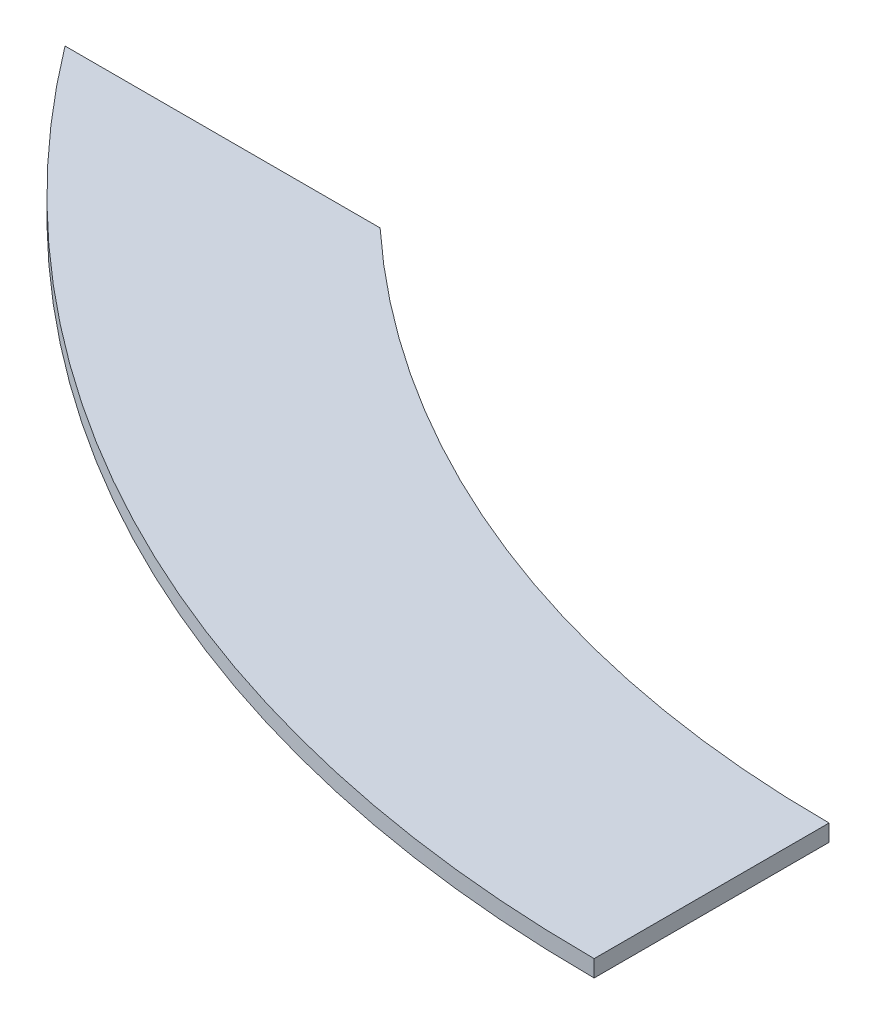
SolidWorks part; units mm, degrees
material "Pine"
ref_plane "Front Plane" through (0, 0, 0) normal (0, 0, 1) x (1, 0, 0)
ref_plane "Top Plane" through (0, 0, 0) normal (0, 1, 0) x (1, 0, 0)
ref_plane "Right Plane" through (0, 0, 0) normal (1, 0, 0) x (0, 0, -1)
sketch "Sketch2" plane through (0, 0, 0) normal (0, 1, 0) x (1, 0, 0)
  line L0 (0, 0) -> (-500, 0)
  line L1 (0, 0) -> (0, -500)
  circle A0 centre (0, 0) radius 500
  circle A1 centre (0, 0) radius 411.1
  dimension "D1" = 1000
  dimension "D2" = 88.9
extrude "Boss-Extrude1" add sketch "Sketch2" along normal blind 6.35 contours A1 L0 A0 L1
sketch "Sketch3" plane through (0, 0, 0) normal (0, 0, -1) x (-1, 0, 0)
  line L8 (411.1, 0) -> (500, 0)
  line L9 (500, 0) -> (500, 6.35)
  line L10 (500, 6.35) -> (411.1, 6.35)
  line L11 (411.1, 6.35) -> (411.1, 0)
  line L12 (411.1, 0) -> (500, 0)
  line L13 (500, 0) -> (500, 6.35)
  line L14 (500, 6.35) -> (411.1, 6.35)
  line L15 (411.1, 6.35) -> (411.1, 0)
  dimension "D1" = 0
extrude "Boss-Extrude2" add sketch "Sketch3" along normal blind 80
sketch "Sketch4" plane through (0, 6.35, 0) normal (0, 1, 0) x (1, 0, 0)
  line L1 (-500, 80) -> (0, 80) construction
  line L2 (-500, 80) -> (-500, -500) construction
  line L3 (-500, -500) -> (0, -500) construction
  line L4 (0, 80) -> (0, -500) construction
  line L5 (-500, 80) -> (-195.2, 80) construction
  line L6 (-500, 80) -> (-500, -326.4) construction
  line L7 (-500, -326.4) -> (-195.2, -326.4) construction
  line L8 (-195.2, 80) -> (-195.2, -326.4) construction
  line L9 (0, -500) -> (-406.4, -500) construction
  line L10 (0, -500) -> (0, -195.2) construction
  line L11 (0, -195.2) -> (-406.4, -195.2) construction
  line L12 (-406.4, -500) -> (-406.4, -195.2) construction
  dimension "D1" = 304.8
  dimension "D2" = 406.4
  dimension "D3" = 304.8
  dimension "D4" = 406.4
ref_plane "Plane1" through (0, 0, 301) normal (0, 0, -1) x (-1, 0, 0)
split "Split1" trim tools "Plane1" bodies to split 102 resulting bodies 103
